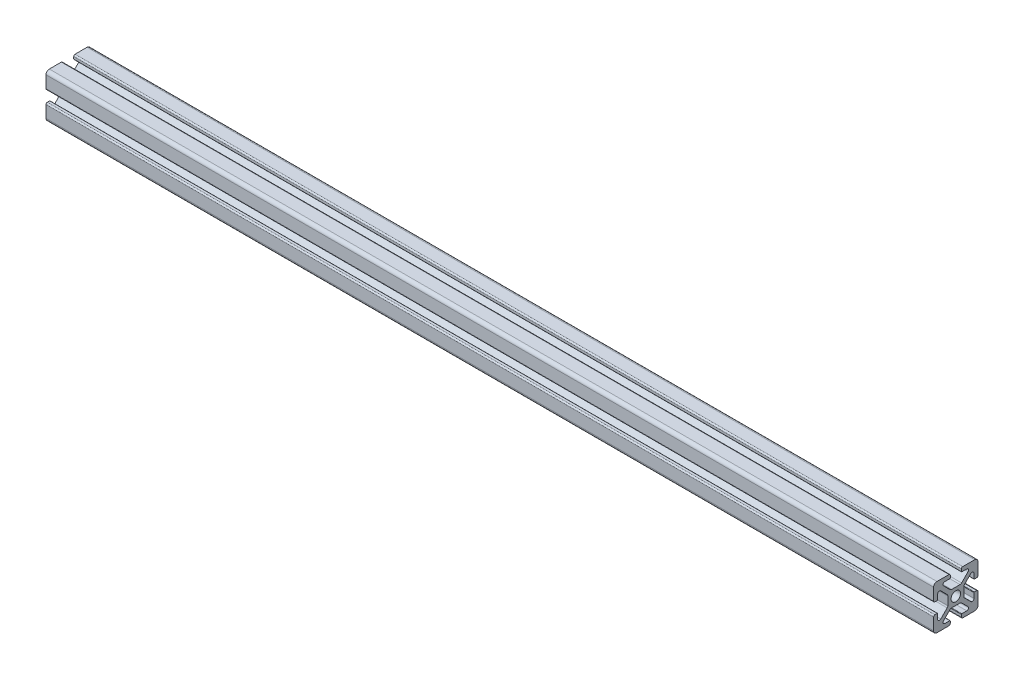
SolidWorks part; units mm, degrees
ref_plane "Front Plane" through (0, 0, 0) normal (0, 0, 1) x (1, 0, 0)
ref_plane "Top Plane" through (0, 0, 0) normal (0, 1, 0) x (1, 0, 0)
ref_plane "Right Plane" through (0, 0, 0) normal (1, 0, 0) x (0, 0, -1)
sketch "Sketch1" plane through (0, 0, 0) normal (1, 0, 0) x (0, 0, -1)
  line L0 (0, -10) -> (0, 10) construction
  line L1 (10, -10) -> (-10, -10)
  line L2 (10, -10) -> (10, 10)
  line L3 (10, 10) -> (0, 10)
  line L4 (-10, -10) -> (-10, 10)
  line L5 (10, -10) -> (-10, 10) construction
  line L6 (10, 10) -> (-10, -10) construction
  line L7 (10, 0) -> (-10, 0) construction
  line L8 (-2.5, 9.4) -> (-2.5, 8.3731)
  line L9 (-2.7, 8.1731) -> (-4.95, 8.1731)
  line L10 (-5.5157, 6.8075) -> (-2.6011, 3.8929)
  line L11 (-1.894, 3.6) -> (0, 3.6)
  line L12 (-5.3502, 4.0584) -> (-4.0584, 5.3502) construction
  line L13 (-3.825, 8.1731) -> (-3.825, 10) construction
  line L14 (-3.1, 10) -> (-10, 10)
  line L15 (-5.75, 7.3731) -> (5.75, 7.3731) construction
  circle A0 centre (0, 0) radius 2.15
  arc A1 (-4.95, 8.1731) -> (-5.5157, 6.8075) centre (-4.95, 7.3731) ccw
  arc A2 (-2.6011, 3.8929) -> (-1.894, 3.6) centre (-1.894, 4.6) ccw
  arc A3 (-2.5, 8.3731) -> (-2.7, 8.1731) centre (-2.7, 8.3731) cw
  arc A4 (-2.5, 9.4) -> (-3.1, 10) centre (-3.1, 9.4) ccw
  point P0 (0, 0)
  point P9 (0, 0)
  point P12 (0, 0)
  point P22 (-4.7043, 4.7043)
  point P32 (-2.5, 10)
  point P33 (-2.5, 8.8866)
  point P35 (-4.0584, 5.3502)
  point P37 (0, 7.3731)
  dimension "Center Hole Diameter" = 4.3
  dimension "D4" = 1
  dimension "D5" = 0.2
  dimension "D6" = 0.6
  dimension "D3" = 0.8
  dimension "Rail Height" = 20
  dimension "D7" = 6.4
  dimension "T Slot Width" = 5
  dimension "D10" = 10
  dimension "Rail Width" = 20
  dimension "D2" = 11.5
sketch "Sketch2" plane through (0, 0, 0) normal (0, 0, 1) x (1, 0, 0)
  line L0 (-132.4, 10) -> (-132.4, -10) construction
  line L1 (152.4, -10) -> (-152.4, -10) construction
  line L2 (152.4, -10) -> (152.4, 10) construction
  line L3 (152.4, 10) -> (-152.4, 10) construction
  line L4 (-152.4, -10) -> (-152.4, 10) construction
  line L5 (152.4, -10) -> (-152.4, 10) construction
  line L6 (152.4, 10) -> (-152.4, -10) construction
  line L7 (132.4, 10) -> (132.4, -10) construction
  point P0 (0, 0)
  point P12 (132.4, 0)
  dimension "Length" = 304.8
  dimension "D1" = 20
  dimension "D2" = 20
sketch "Sketch3" plane through (0, 0, 0) normal (1, 0, 0) x (0, 0, -1)
  line L0 (-5.5157, 6.8075) -> (-2.6011, 3.8929) construction
  line L5 (-3.1, 10) -> (-10, 10) construction
  line L6 (-2.5, 9.4) -> (-2.5, 8.3731) construction
  line L7 (-2.7, 8.1731) -> (-4.95, 8.1731) construction
  line L8 (-1.894, 3.6) -> (0, 3.6) construction
  line L9 (-5.5157, 6.8075) -> (-2.6011, 3.8929)
  line L10 (-10, 10) -> (0, 0) construction
  line L12 (-3.6, 1.894) -> (-3.6, 0)
  line L13 (-8.1731, 2.7) -> (-8.1731, 4.95)
  line L14 (-3.1, 10) -> (-8.5, 10)
  line L15 (-2.5, 9.4) -> (-2.5, 8.3731)
  line L16 (-2.7, 8.1731) -> (-4.95, 8.1731)
  line L17 (-1.894, 3.6) -> (0, 3.6)
  line L18 (-9.4, 2.5) -> (-8.3731, 2.5)
  line L19 (-10, 3.1) -> (-10, 8.5)
  line L20 (-6.8075, 5.5157) -> (-3.8929, 2.6011)
  line L21 (-3.6, 0) -> (-2.15, 0)
  line L22 (0, 3.6) -> (0, 2.15)
  arc A0 (-2.5, 9.4) -> (-3.1, 10) centre (-3.1, 9.4) ccw construction
  arc A1 (-2.7, 8.1731) -> (-2.5, 8.3731) centre (-2.7, 8.3731) ccw construction
  arc A2 (-4.95, 8.1731) -> (-5.5157, 6.8075) centre (-4.95, 7.3731) ccw construction
  arc A3 (-2.6011, 3.8929) -> (-1.894, 3.6) centre (-1.894, 4.6) ccw construction
  arc A4 (-2.5, 9.4) -> (-3.1, 10) centre (-3.1, 9.4) ccw
  arc A5 (-2.7, 8.1731) -> (-2.5, 8.3731) centre (-2.7, 8.3731) ccw
  arc A6 (-4.95, 8.1731) -> (-5.5157, 6.8075) centre (-4.95, 7.3731) ccw
  arc A7 (-2.6011, 3.8929) -> (-1.894, 3.6) centre (-1.894, 4.6) ccw
  arc A8 (-3.8929, 2.6011) -> (-3.6, 1.894) centre (-4.6, 1.894) cw
  arc A9 (-8.1731, 4.95) -> (-6.8075, 5.5157) centre (-7.3731, 4.95) cw
  arc A10 (-8.1731, 2.7) -> (-8.3731, 2.5) centre (-8.3731, 2.7) cw
  arc A11 (-9.4, 2.5) -> (-10, 3.1) centre (-9.4, 3.1) cw
  circle A12 centre (0, 0) radius 2.15 construction
  arc A13 (0, 2.15) -> (-2.15, 0) centre (0, 0) ccw
  arc A14 (-10, 8.5) -> (-8.5, 10) centre (-8.5, 8.5) cw
  dimension "D1" = 1.5
extrude "Boss-Extrude1" add sketch "Sketch3" against normal up to vertex (152.4 mm away) and the other way up to vertex (152.4 mm away) up to point (-152.4, 10, 0) other way up to point (152.4, 10, 0)
mirror "Mirror1" about plane through (0, 0, 0) normal (0, 1, 0) of bodies 104
mirror "Mirror2" about plane through (0, 0, 0) normal (0, 0, 1) of bodies 105
sketch "Sketch4" plane through (152.4, 0, 0) normal (1, 0, 0) x (0, 0, -1)
  line L36 (1.894, 3.6) -> (-1.894, 3.6)
  line L37 (-2.6011, 3.8929) -> (-5.5157, 6.8075)
  line L38 (-4.95, 8.1731) -> (-2.7, 8.1731)
  line L39 (-2.5, 8.3731) -> (-2.5, 9.4)
  line L40 (-3.1, 10) -> (-8.5, 10)
  line L41 (-10, 8.5) -> (-10, 3.1)
  line L42 (-9.4, 2.5) -> (-8.3731, 2.5)
  line L43 (-8.1731, 2.7) -> (-8.1731, 4.95)
  line L44 (-6.8075, 5.5157) -> (-3.8929, 2.6011)
  line L45 (-3.6, 1.894) -> (-3.6, -1.894)
  line L46 (-3.8929, -2.6011) -> (-6.8075, -5.5157)
  line L47 (-8.1731, -4.95) -> (-8.1731, -2.7)
  line L48 (-8.3731, -2.5) -> (-9.4, -2.5)
  line L49 (-10, -3.1) -> (-10, -8.5)
  line L50 (-8.5, -10) -> (-3.1, -10)
  line L51 (-2.5, -9.4) -> (-2.5, -8.3731)
  line L52 (-2.7, -8.1731) -> (-4.95, -8.1731)
  line L53 (-5.5157, -6.8075) -> (-2.6011, -3.8929)
  line L54 (-1.894, -3.6) -> (1.894, -3.6)
  line L55 (2.6011, -3.8929) -> (5.5157, -6.8075)
  line L56 (4.95, -8.1731) -> (2.7, -8.1731)
  line L57 (2.5, -8.3731) -> (2.5, -9.4)
  line L58 (3.1, -10) -> (8.5, -10)
  line L59 (10, -8.5) -> (10, -3.1)
  line L60 (9.4, -2.5) -> (8.3731, -2.5)
  line L61 (8.1731, -2.7) -> (8.1731, -4.95)
  line L62 (6.8075, -5.5157) -> (3.8929, -2.6011)
  line L63 (3.6, -1.894) -> (3.6, 1.894)
  line L64 (3.8929, 2.6011) -> (6.8075, 5.5157)
  line L65 (8.1731, 4.95) -> (8.1731, 2.7)
  line L66 (8.3731, 2.5) -> (9.4, 2.5)
  line L67 (10, 3.1) -> (10, 8.5)
  line L68 (8.5, 10) -> (3.1, 10)
  line L69 (2.5, 9.4) -> (2.5, 8.3731)
  line L70 (2.7, 8.1731) -> (4.95, 8.1731)
  line L71 (5.5157, 6.8075) -> (2.6011, 3.8929)
  line L72 (1.894, 3.6) -> (-1.894, 3.6)
  line L73 (-2.6011, 3.8929) -> (-5.5157, 6.8075)
  line L74 (-4.95, 8.1731) -> (-2.7, 8.1731)
  line L75 (-2.5, 8.3731) -> (-2.5, 9.4)
  line L76 (-3.1, 10) -> (-8.5, 10)
  line L77 (-10, 8.5) -> (-10, 3.1)
  line L78 (-9.4, 2.5) -> (-8.3731, 2.5)
  line L79 (-8.1731, 2.7) -> (-8.1731, 4.95)
  line L80 (-6.8075, 5.5157) -> (-3.8929, 2.6011)
  line L81 (-3.6, 1.894) -> (-3.6, -1.894)
  line L82 (-3.8929, -2.6011) -> (-6.8075, -5.5157)
  line L83 (-8.1731, -4.95) -> (-8.1731, -2.7)
  line L84 (-8.3731, -2.5) -> (-9.4, -2.5)
  line L85 (-10, -3.1) -> (-10, -8.5)
  line L86 (-8.5, -10) -> (-3.1, -10)
  line L87 (-2.5, -9.4) -> (-2.5, -8.3731)
  line L88 (-2.7, -8.1731) -> (-4.95, -8.1731)
  line L89 (-5.5157, -6.8075) -> (-2.6011, -3.8929)
  line L90 (-1.894, -3.6) -> (1.894, -3.6)
  line L91 (2.6011, -3.8929) -> (5.5157, -6.8075)
  line L92 (4.95, -8.1731) -> (2.7, -8.1731)
  line L93 (2.5, -8.3731) -> (2.5, -9.4)
  line L94 (3.1, -10) -> (8.5, -10)
  line L95 (10, -8.5) -> (10, -3.1)
  line L96 (9.4, -2.5) -> (8.3731, -2.5)
  line L97 (8.1731, -2.7) -> (8.1731, -4.95)
  line L98 (6.8075, -5.5157) -> (3.8929, -2.6011)
  line L99 (3.6, -1.894) -> (3.6, 1.894)
  line L100 (3.8929, 2.6011) -> (6.8075, 5.5157)
  line L101 (8.1731, 4.95) -> (8.1731, 2.7)
  line L102 (8.3731, 2.5) -> (9.4, 2.5)
  line L103 (10, 3.1) -> (10, 8.5)
  line L104 (8.5, 10) -> (3.1, 10)
  line L105 (2.5, 9.4) -> (2.5, 8.3731)
  line L106 (2.7, 8.1731) -> (4.95, 8.1731)
  line L107 (5.5157, 6.8075) -> (2.6011, 3.8929)
  circle A0 centre (0, 0) radius 2.15 construction
  circle A1 centre (0, 0) radius 2.15
  arc A36 (1.894, 3.6) -> (2.6011, 3.8929) centre (1.894, 4.6) ccw
  arc A37 (-2.6011, 3.8929) -> (-1.894, 3.6) centre (-1.894, 4.6) ccw
  arc A38 (-4.95, 8.1731) -> (-5.5157, 6.8075) centre (-4.95, 7.3731) ccw
  arc A39 (-2.7, 8.1731) -> (-2.5, 8.3731) centre (-2.7, 8.3731) ccw
  arc A40 (-2.5, 9.4) -> (-3.1, 10) centre (-3.1, 9.4) ccw
  arc A41 (-8.5, 10) -> (-10, 8.5) centre (-8.5, 8.5) ccw
  arc A42 (-10, 3.1) -> (-9.4, 2.5) centre (-9.4, 3.1) ccw
  arc A43 (-8.3731, 2.5) -> (-8.1731, 2.7) centre (-8.3731, 2.7) ccw
  arc A44 (-6.8075, 5.5157) -> (-8.1731, 4.95) centre (-7.3731, 4.95) ccw
  arc A45 (-3.6, 1.894) -> (-3.8929, 2.6011) centre (-4.6, 1.894) ccw
  arc A46 (-3.8929, -2.6011) -> (-3.6, -1.894) centre (-4.6, -1.894) ccw
  arc A47 (-8.1731, -4.95) -> (-6.8075, -5.5157) centre (-7.3731, -4.95) ccw
  arc A48 (-8.1731, -2.7) -> (-8.3731, -2.5) centre (-8.3731, -2.7) ccw
  arc A49 (-9.4, -2.5) -> (-10, -3.1) centre (-9.4, -3.1) ccw
  arc A50 (-10, -8.5) -> (-8.5, -10) centre (-8.5, -8.5) ccw
  arc A51 (-3.1, -10) -> (-2.5, -9.4) centre (-3.1, -9.4) ccw
  arc A52 (-2.5, -8.3731) -> (-2.7, -8.1731) centre (-2.7, -8.3731) ccw
  arc A53 (-5.5157, -6.8075) -> (-4.95, -8.1731) centre (-4.95, -7.3731) ccw
  arc A54 (-1.894, -3.6) -> (-2.6011, -3.8929) centre (-1.894, -4.6) ccw
  arc A55 (2.6011, -3.8929) -> (1.894, -3.6) centre (1.894, -4.6) ccw
  arc A56 (4.95, -8.1731) -> (5.5157, -6.8075) centre (4.95, -7.3731) ccw
  arc A57 (2.7, -8.1731) -> (2.5, -8.3731) centre (2.7, -8.3731) ccw
  arc A58 (2.5, -9.4) -> (3.1, -10) centre (3.1, -9.4) ccw
  arc A59 (8.5, -10) -> (10, -8.5) centre (8.5, -8.5) ccw
  arc A60 (10, -3.1) -> (9.4, -2.5) centre (9.4, -3.1) ccw
  arc A61 (8.3731, -2.5) -> (8.1731, -2.7) centre (8.3731, -2.7) ccw
  arc A62 (6.8075, -5.5157) -> (8.1731, -4.95) centre (7.3731, -4.95) ccw
  arc A63 (3.6, -1.894) -> (3.8929, -2.6011) centre (4.6, -1.894) ccw
  arc A64 (3.8929, 2.6011) -> (3.6, 1.894) centre (4.6, 1.894) ccw
  arc A65 (8.1731, 4.95) -> (6.8075, 5.5157) centre (7.3731, 4.95) ccw
  arc A66 (8.1731, 2.7) -> (8.3731, 2.5) centre (8.3731, 2.7) ccw
  arc A67 (9.4, 2.5) -> (10, 3.1) centre (9.4, 3.1) ccw
  arc A68 (10, 8.5) -> (8.5, 10) centre (8.5, 8.5) ccw
  arc A69 (3.1, 10) -> (2.5, 9.4) centre (3.1, 9.4) ccw
  arc A70 (2.5, 8.3731) -> (2.7, 8.1731) centre (2.7, 8.3731) ccw
  arc A71 (5.5157, 6.8075) -> (4.95, 8.1731) centre (4.95, 7.3731) ccw
  arc A72 (1.894, 3.6) -> (2.6011, 3.8929) centre (1.894, 4.6) ccw
  arc A73 (-2.6011, 3.8929) -> (-1.894, 3.6) centre (-1.894, 4.6) ccw
  arc A74 (-4.95, 8.1731) -> (-5.5157, 6.8075) centre (-4.95, 7.3731) ccw
  arc A75 (-2.7, 8.1731) -> (-2.5, 8.3731) centre (-2.7, 8.3731) ccw
  arc A76 (-2.5, 9.4) -> (-3.1, 10) centre (-3.1, 9.4) ccw
  arc A77 (-8.5, 10) -> (-10, 8.5) centre (-8.5, 8.5) ccw
  arc A78 (-10, 3.1) -> (-9.4, 2.5) centre (-9.4, 3.1) ccw
  arc A79 (-8.3731, 2.5) -> (-8.1731, 2.7) centre (-8.3731, 2.7) ccw
  arc A80 (-6.8075, 5.5157) -> (-8.1731, 4.95) centre (-7.3731, 4.95) ccw
  arc A81 (-3.6, 1.894) -> (-3.8929, 2.6011) centre (-4.6, 1.894) ccw
  arc A82 (-3.8929, -2.6011) -> (-3.6, -1.894) centre (-4.6, -1.894) ccw
  arc A83 (-8.1731, -4.95) -> (-6.8075, -5.5157) centre (-7.3731, -4.95) ccw
  arc A84 (-8.1731, -2.7) -> (-8.3731, -2.5) centre (-8.3731, -2.7) ccw
  arc A85 (-9.4, -2.5) -> (-10, -3.1) centre (-9.4, -3.1) ccw
  arc A86 (-10, -8.5) -> (-8.5, -10) centre (-8.5, -8.5) ccw
  arc A87 (-3.1, -10) -> (-2.5, -9.4) centre (-3.1, -9.4) ccw
  arc A88 (-2.5, -8.3731) -> (-2.7, -8.1731) centre (-2.7, -8.3731) ccw
  arc A89 (-5.5157, -6.8075) -> (-4.95, -8.1731) centre (-4.95, -7.3731) ccw
  arc A90 (-1.894, -3.6) -> (-2.6011, -3.8929) centre (-1.894, -4.6) ccw
  arc A91 (2.6011, -3.8929) -> (1.894, -3.6) centre (1.894, -4.6) ccw
  arc A92 (4.95, -8.1731) -> (5.5157, -6.8075) centre (4.95, -7.3731) ccw
  arc A93 (2.7, -8.1731) -> (2.5, -8.3731) centre (2.7, -8.3731) ccw
  arc A94 (2.5, -9.4) -> (3.1, -10) centre (3.1, -9.4) ccw
  arc A95 (8.5, -10) -> (10, -8.5) centre (8.5, -8.5) ccw
  arc A96 (10, -3.1) -> (9.4, -2.5) centre (9.4, -3.1) ccw
  arc A97 (8.3731, -2.5) -> (8.1731, -2.7) centre (8.3731, -2.7) ccw
  arc A98 (6.8075, -5.5157) -> (8.1731, -4.95) centre (7.3731, -4.95) ccw
  arc A99 (3.6, -1.894) -> (3.8929, -2.6011) centre (4.6, -1.894) ccw
  arc A100 (3.8929, 2.6011) -> (3.6, 1.894) centre (4.6, 1.894) ccw
  arc A101 (8.1731, 4.95) -> (6.8075, 5.5157) centre (7.3731, 4.95) ccw
  arc A102 (8.1731, 2.7) -> (8.3731, 2.5) centre (8.3731, 2.7) ccw
  arc A103 (9.4, 2.5) -> (10, 3.1) centre (9.4, 3.1) ccw
  arc A104 (10, 8.5) -> (8.5, 10) centre (8.5, 8.5) ccw
  arc A105 (3.1, 10) -> (2.5, 9.4) centre (3.1, 9.4) ccw
  arc A106 (2.5, 8.3731) -> (2.7, 8.1731) centre (2.7, 8.3731) ccw
  arc A107 (5.5157, 6.8075) -> (4.95, 8.1731) centre (4.95, 7.3731) ccw
  dimension "D1" = 0
extrude "Boss-Extrude2" add sketch "Sketch4" along normal offset from surface (95.2 mm away) 400 up to face at (-152.4, 0, 0)
equation "\"D10@Sketch1\" = \"Rail Height@Sketch1\" / 2"
equation "\"D2@Sketch2\"=\"D1@Sketch2\""
